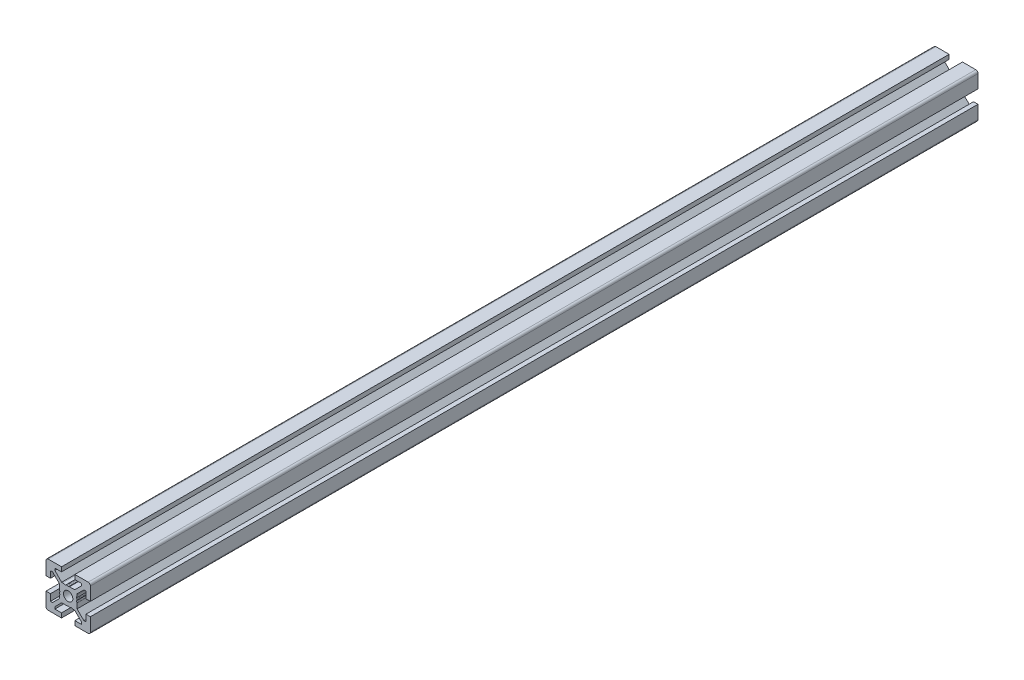
SolidWorks part; units mm, degrees
ref_plane "Front Plane" through (0, 0, 0) normal (0, 0, 1) x (1, 0, 0)
ref_plane "Top Plane" through (0, 0, 0) normal (0, 1, 0) x (1, 0, 0)
ref_plane "Right Plane" through (0, 0, 0) normal (1, 0, 0) x (0, 0, -1)
ref_plane "Plane1" through (0, 0, -2000) normal (0, 0, -1) x (-1, 0, 0)
sketch "Sketch1" plane through (0, 0, -2000) normal (0, 0, -1) x (-1, 0, 0)
  line L0 (10, -3) -> (8, -3)
  line L1 (8, -3) -> (8, -6)
  line L2 (8, -6) -> (7.0607, -6)
  line L3 (7.0607, -6) -> (4, -2.9393)
  line L4 (4, -2.9393) -> (4, -2.5)
  line L5 (4, -2.5) -> (3.751, -1.2189)
  line L6 (3.751, -1.2189) -> (3.933, -0.9036)
  line L7 (3.933, -0.4036) -> (3.7, 0)
  line L8 (3.7, 0) -> (3.933, 0.4036)
  line L9 (4, 0.6536) -> (4, 2.9393)
  line L10 (4, 2.9393) -> (7.0607, 6)
  line L11 (7.0607, 6) -> (8, 6)
  line L12 (8, 6) -> (8, 3)
  line L13 (8, 3) -> (10, 3)
  line L14 (10, 3) -> (10, 9)
  line L15 (9, 10) -> (3, 10)
  line L16 (3, 10) -> (3, 8)
  line L17 (3, 8) -> (6, 8)
  line L18 (6, 8) -> (6, 7.0607)
  line L19 (6, 7.0607) -> (2.9393, 4)
  line L20 (2.9393, 4) -> (2.5, 4)
  line L21 (2.5, 4) -> (1.2189, 3.751)
  line L22 (1.2189, 3.751) -> (0.9036, 3.933)
  line L23 (0.4036, 3.933) -> (0, 3.7)
  line L24 (0, 3.7) -> (-0.4036, 3.933)
  line L25 (-0.6536, 4) -> (-2.9393, 4)
  line L26 (-2.9393, 4) -> (-6, 7.0607)
  line L27 (-6, 7.0607) -> (-6, 8)
  line L28 (-6, 8) -> (-3, 8)
  line L29 (-3, 8) -> (-3, 10)
  line L30 (-3, 10) -> (-9, 10)
  line L31 (-10, 9) -> (-10, 3)
  line L32 (-10, 3) -> (-8, 3)
  line L33 (-8, 3) -> (-8, 6)
  line L34 (-8, 6) -> (-7.0607, 6)
  line L35 (-7.0607, 6) -> (-4, 2.9393)
  line L36 (-4, 2.9393) -> (-4, 2.5)
  line L37 (-4, 2.5) -> (-3.751, 1.2189)
  line L38 (-3.751, 1.2189) -> (-3.933, 0.9036)
  line L39 (-3.933, 0.4036) -> (-3.7, 0)
  line L40 (-3.7, 0) -> (-3.933, -0.4036)
  line L41 (-4, -0.6536) -> (-4, -2.9393)
  line L42 (-4, -2.9393) -> (-7.0607, -6)
  line L43 (-7.0607, -6) -> (-8, -6)
  line L44 (-8, -6) -> (-8, -3)
  line L45 (-8, -3) -> (-10, -3)
  line L46 (-10, -3) -> (-10, -9)
  line L47 (-9, -10) -> (-3, -10)
  line L48 (-3, -10) -> (-3, -8)
  line L49 (-3, -8) -> (-6, -8)
  line L50 (-6, -8) -> (-6, -7.0607)
  line L51 (-6, -7.0607) -> (-2.9393, -4)
  line L52 (-2.9393, -4) -> (-2.5, -4)
  line L53 (-2.5, -4) -> (-1.2189, -3.751)
  line L54 (-1.2189, -3.751) -> (-0.9036, -3.933)
  line L55 (-0.4036, -3.933) -> (0, -3.7)
  line L56 (0, -3.7) -> (0.4036, -3.933)
  line L57 (0.6536, -4) -> (2.9393, -4)
  line L58 (2.9393, -4) -> (6, -7.0607)
  line L59 (6, -7.0607) -> (6, -8)
  line L60 (6, -8) -> (3, -8)
  line L61 (3, -8) -> (3, -10)
  line L62 (3, -10) -> (9, -10)
  line L63 (10, -9) -> (10, -3)
  circle A0 centre (0, 0) radius 2.1
  arc A1 (3.933, -0.9036) -> (3.933, -0.4036) centre (3.5, -0.6536) ccw
  arc A2 (3.933, 0.4036) -> (4, 0.6536) centre (3.5, 0.6536) ccw
  arc A3 (10, 9) -> (9, 10) centre (9, 9) ccw
  arc A4 (0.9036, 3.933) -> (0.4036, 3.933) centre (0.6536, 3.5) ccw
  arc A5 (-0.4036, 3.933) -> (-0.6536, 4) centre (-0.6536, 3.5) ccw
  arc A6 (-9, 10) -> (-10, 9) centre (-9, 9) ccw
  arc A7 (-3.933, 0.9036) -> (-3.933, 0.4036) centre (-3.5, 0.6536) ccw
  arc A8 (-3.933, -0.4036) -> (-4, -0.6536) centre (-3.5, -0.6536) ccw
  arc A9 (-10, -9) -> (-9, -10) centre (-9, -9) ccw
  arc A10 (-0.9036, -3.933) -> (-0.4036, -3.933) centre (-0.6536, -3.5) ccw
  arc A11 (0.4036, -3.933) -> (0.6536, -4) centre (0.6536, -3.5) ccw
  arc A12 (9, -10) -> (10, -9) centre (9, -9) ccw
extrude "Boss-Extrude1" add sketch "Sketch1" against normal blind 400
sketch "草图1" plane through (0, 0, -1600) normal (0, 0, 1) x (1, 0, 0)
  line L64 (-10, -3) -> (-10, -9)
  line L65 (-8, -3) -> (-10, -3)
  line L66 (-8, -6) -> (-8, -3)
  line L67 (-7.0607, -6) -> (-8, -6)
  line L68 (-4, -2.9393) -> (-7.0607, -6)
  line L69 (-4, -2.5) -> (-4, -2.9393)
  line L70 (-3.751, -1.2189) -> (-4, -2.5)
  line L71 (-3.933, -0.9036) -> (-3.751, -1.2189)
  line L72 (-3.7, 0) -> (-3.933, -0.4036)
  line L73 (-3.933, 0.4036) -> (-3.7, 0)
  line L74 (-4, 2.9393) -> (-4, 0.6536)
  line L75 (-7.0607, 6) -> (-4, 2.9393)
  line L76 (-8, 6) -> (-7.0607, 6)
  line L77 (-8, 3) -> (-8, 6)
  line L78 (-10, 3) -> (-8, 3)
  line L79 (-10, 9) -> (-10, 3)
  line L80 (-3, 10) -> (-9, 10)
  line L81 (-3, 8) -> (-3, 10)
  line L82 (-6, 8) -> (-3, 8)
  line L83 (-6, 7.0607) -> (-6, 8)
  line L84 (-2.9393, 4) -> (-6, 7.0607)
  line L85 (-2.5, 4) -> (-2.9393, 4)
  line L86 (-1.2189, 3.751) -> (-2.5, 4)
  line L87 (-0.9036, 3.933) -> (-1.2189, 3.751)
  line L88 (0, 3.7) -> (-0.4036, 3.933)
  line L89 (0.4036, 3.933) -> (0, 3.7)
  line L90 (2.9393, 4) -> (0.6536, 4)
  line L91 (6, 7.0607) -> (2.9393, 4)
  line L92 (6, 8) -> (6, 7.0607)
  line L93 (3, 8) -> (6, 8)
  line L94 (3, 10) -> (3, 8)
  line L95 (9, 10) -> (3, 10)
  line L96 (10, 3) -> (10, 9)
  line L97 (8, 3) -> (10, 3)
  line L98 (8, 6) -> (8, 3)
  line L99 (7.0607, 6) -> (8, 6)
  line L100 (4, 2.9393) -> (7.0607, 6)
  line L101 (4, 2.5) -> (4, 2.9393)
  line L102 (3.751, 1.2189) -> (4, 2.5)
  line L103 (3.933, 0.9036) -> (3.751, 1.2189)
  line L104 (3.7, 0) -> (3.933, 0.4036)
  line L105 (3.933, -0.4036) -> (3.7, 0)
  line L106 (4, -2.9393) -> (4, -0.6536)
  line L107 (7.0607, -6) -> (4, -2.9393)
  line L108 (8, -6) -> (7.0607, -6)
  line L109 (8, -3) -> (8, -6)
  line L110 (10, -3) -> (8, -3)
  line L111 (10, -9) -> (10, -3)
  line L112 (3, -10) -> (9, -10)
  line L113 (3, -8) -> (3, -10)
  line L114 (6, -8) -> (3, -8)
  line L115 (6, -7.0607) -> (6, -8)
  line L116 (2.9393, -4) -> (6, -7.0607)
  line L117 (2.5, -4) -> (2.9393, -4)
  line L118 (1.2189, -3.751) -> (2.5, -4)
  line L119 (0.9036, -3.933) -> (1.2189, -3.751)
  line L120 (0, -3.7) -> (0.4036, -3.933)
  line L121 (-0.4036, -3.933) -> (0, -3.7)
  line L122 (-2.9393, -4) -> (-0.6536, -4)
  line L123 (-6, -7.0607) -> (-2.9393, -4)
  line L124 (-6, -8) -> (-6, -7.0607)
  line L125 (-3, -8) -> (-6, -8)
  line L126 (-3, -10) -> (-3, -8)
  line L127 (-9, -10) -> (-3, -10)
  line L128 (-10, -3) -> (-10, -9)
  line L129 (-8, -3) -> (-10, -3)
  line L130 (-8, -6) -> (-8, -3)
  line L131 (-7.0607, -6) -> (-8, -6)
  line L132 (-4, -2.9393) -> (-7.0607, -6)
  line L133 (-4, -2.5) -> (-4, -2.9393)
  line L134 (-3.751, -1.2189) -> (-4, -2.5)
  line L135 (-3.933, -0.9036) -> (-3.751, -1.2189)
  line L136 (-3.7, 0) -> (-3.933, -0.4036)
  line L137 (-3.933, 0.4036) -> (-3.7, 0)
  line L138 (-4, 2.9393) -> (-4, 0.6536)
  line L139 (-7.0607, 6) -> (-4, 2.9393)
  line L140 (-8, 6) -> (-7.0607, 6)
  line L141 (-8, 3) -> (-8, 6)
  line L142 (-10, 3) -> (-8, 3)
  line L143 (-10, 9) -> (-10, 3)
  line L144 (-3, 10) -> (-9, 10)
  line L145 (-3, 8) -> (-3, 10)
  line L146 (-6, 8) -> (-3, 8)
  line L147 (-6, 7.0607) -> (-6, 8)
  line L148 (-2.9393, 4) -> (-6, 7.0607)
  line L149 (-2.5, 4) -> (-2.9393, 4)
  line L150 (-1.2189, 3.751) -> (-2.5, 4)
  line L151 (-0.9036, 3.933) -> (-1.2189, 3.751)
  line L152 (0, 3.7) -> (-0.4036, 3.933)
  line L153 (0.4036, 3.933) -> (0, 3.7)
  line L154 (2.9393, 4) -> (0.6536, 4)
  line L155 (6, 7.0607) -> (2.9393, 4)
  line L156 (6, 8) -> (6, 7.0607)
  line L157 (3, 8) -> (6, 8)
  line L158 (3, 10) -> (3, 8)
  line L159 (9, 10) -> (3, 10)
  line L160 (10, 3) -> (10, 9)
  line L161 (8, 3) -> (10, 3)
  line L162 (8, 6) -> (8, 3)
  line L163 (7.0607, 6) -> (8, 6)
  line L164 (4, 2.9393) -> (7.0607, 6)
  line L165 (4, 2.5) -> (4, 2.9393)
  line L166 (3.751, 1.2189) -> (4, 2.5)
  line L167 (3.933, 0.9036) -> (3.751, 1.2189)
  line L168 (3.7, 0) -> (3.933, 0.4036)
  line L169 (3.933, -0.4036) -> (3.7, 0)
  line L170 (4, -2.9393) -> (4, -0.6536)
  line L171 (7.0607, -6) -> (4, -2.9393)
  line L172 (8, -6) -> (7.0607, -6)
  line L173 (8, -3) -> (8, -6)
  line L174 (10, -3) -> (8, -3)
  line L175 (10, -9) -> (10, -3)
  line L176 (3, -10) -> (9, -10)
  line L177 (3, -8) -> (3, -10)
  line L178 (6, -8) -> (3, -8)
  line L179 (6, -7.0607) -> (6, -8)
  line L180 (2.9393, -4) -> (6, -7.0607)
  line L181 (2.5, -4) -> (2.9393, -4)
  line L182 (1.2189, -3.751) -> (2.5, -4)
  line L183 (0.9036, -3.933) -> (1.2189, -3.751)
  line L184 (0, -3.7) -> (0.4036, -3.933)
  line L185 (-0.4036, -3.933) -> (0, -3.7)
  line L186 (-2.9393, -4) -> (-0.6536, -4)
  line L187 (-6, -7.0607) -> (-2.9393, -4)
  line L188 (-6, -8) -> (-6, -7.0607)
  line L189 (-3, -8) -> (-6, -8)
  line L190 (-3, -10) -> (-3, -8)
  line L191 (-9, -10) -> (-3, -10)
  arc A12 (-3.933, -0.4036) -> (-3.933, -0.9036) centre (-3.5, -0.6536) ccw
  arc A13 (-4, 0.6536) -> (-3.933, 0.4036) centre (-3.5, 0.6536) ccw
  arc A14 (-9, 10) -> (-10, 9) centre (-9, 9) ccw
  arc A15 (-0.4036, 3.933) -> (-0.9036, 3.933) centre (-0.6536, 3.5) ccw
  arc A16 (0.6536, 4) -> (0.4036, 3.933) centre (0.6536, 3.5) ccw
  arc A17 (10, 9) -> (9, 10) centre (9, 9) ccw
  arc A18 (3.933, 0.4036) -> (3.933, 0.9036) centre (3.5, 0.6536) ccw
  arc A19 (4, -0.6536) -> (3.933, -0.4036) centre (3.5, -0.6536) ccw
  arc A20 (9, -10) -> (10, -9) centre (9, -9) ccw
  arc A21 (0.4036, -3.933) -> (0.9036, -3.933) centre (0.6536, -3.5) ccw
  arc A22 (-0.6536, -4) -> (-0.4036, -3.933) centre (-0.6536, -3.5) ccw
  arc A23 (-10, -9) -> (-9, -10) centre (-9, -9) ccw
  arc A24 (-3.933, -0.4036) -> (-3.933, -0.9036) centre (-3.5, -0.6536) ccw
  arc A25 (-4, 0.6536) -> (-3.933, 0.4036) centre (-3.5, 0.6536) ccw
  arc A26 (-9, 10) -> (-10, 9) centre (-9, 9) ccw
  arc A27 (-0.4036, 3.933) -> (-0.9036, 3.933) centre (-0.6536, 3.5) ccw
  arc A28 (0.6536, 4) -> (0.4036, 3.933) centre (0.6536, 3.5) ccw
  arc A29 (10, 9) -> (9, 10) centre (9, 9) ccw
  arc A30 (3.933, 0.4036) -> (3.933, 0.9036) centre (3.5, 0.6536) ccw
  arc A31 (4, -0.6536) -> (3.933, -0.4036) centre (3.5, -0.6536) ccw
  arc A32 (9, -10) -> (10, -9) centre (9, -9) ccw
  arc A33 (0.4036, -3.933) -> (0.9036, -3.933) centre (0.6536, -3.5) ccw
  arc A34 (-0.6536, -4) -> (-0.4036, -3.933) centre (-0.6536, -3.5) ccw
  arc A35 (-10, -9) -> (-9, -10) centre (-9, -9) ccw
  dimension "D1" = 0
